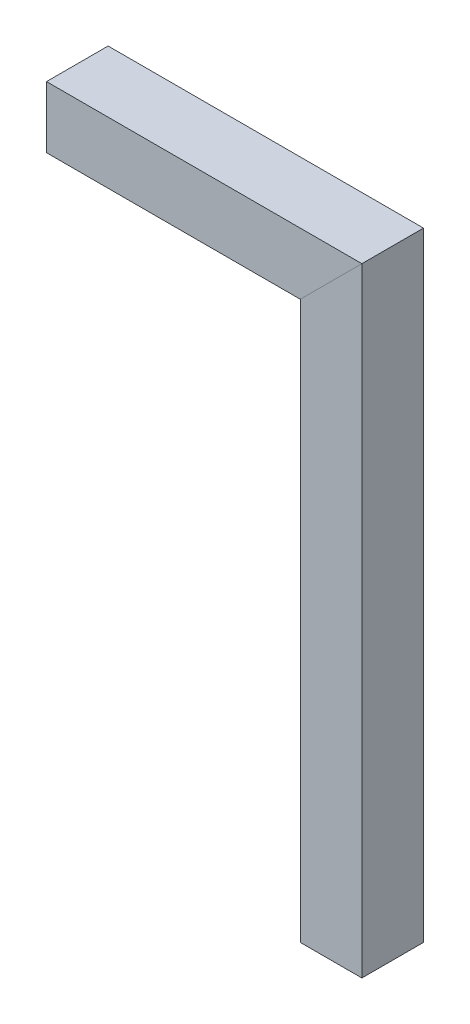
SolidWorks part; units mm, degrees
material "Fundición gris (SN)"
ref_plane "Alzado" through (0, 0, 0) normal (0, 0, 1) x (1, 0, 0)
ref_plane "Planta" through (0, 0, 0) normal (0, 1, 0) x (1, 0, 0)
ref_plane "Vista lateral" through (0, 0, 0) normal (1, 0, 0) x (0, 0, -1)
sketch "Croquis1" plane through (0, 0, 0) normal (0, 0, 1) x (1, 0, 0)
  line L0 (0, 0) -> (-260, 0)
  line L1 (0, 0) -> (0, -510)
  dimension "D1" = 260
  dimension "D2" = 510
other "Hierro angular 2 X 2 X 0.125(1)"
ref_plane "Plano1" through (0, 0, 0) normal (-1, 0, 0) x (0, 0, -1)
sketch "Sketch1" plane through (0, 0, 0) normal (-1, 0, 0) x (0, 0, -1)
  line L0 (0, 0) -> (0, 50.8)
  line L1 (0, 50.8) -> (0.0051, 50.8)
  line L2 (3.175, 47.6301) -> (3.175, 7.9375)
  line L3 (7.9375, 3.175) -> (47.6301, 3.175)
  line L4 (50.8, 0.0051) -> (50.8, 0)
  line L5 (50.8, 0) -> (0, 0)
  arc A0 (50.8, 0.0051) -> (47.6301, 3.175) centre (47.6301, 0.0051) ccw
  arc A1 (0.0051, 50.8) -> (3.175, 47.6301) centre (0.0051, 47.6301) cw
  arc A2 (7.9375, 3.175) -> (3.175, 7.9375) centre (7.9375, 7.9375) cw
  point P10 (25.4, 0)
  point P14 (0, 25.4)
  point P15 (3.175, 25.4)
  point P16 (25.4, 3.175)
  point P17 (3.175, 50.8)
  point P18 (50.8, 3.175)
  point P19 (0, 0)
  dimension "D2" = 0.0051
  dimension "Radius_1" = 4.7625
  dimension "D1" = 3.175
  dimension "H_leg" = 50.8
